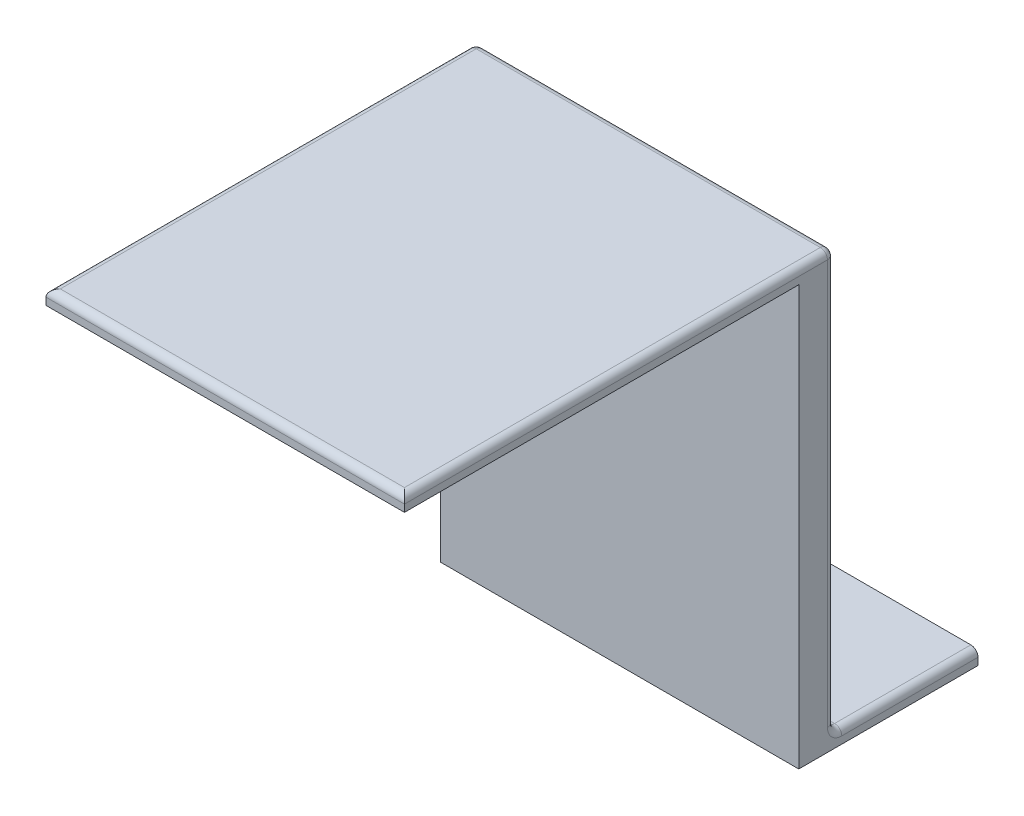
SolidWorks part; units mm, degrees
ref_plane "前视基准面" through (0, 0, 0) normal (0, 0, 1) x (1, 0, 0)
ref_plane "上视基准面" through (0, 0, 0) normal (0, 1, 0) x (1, 0, 0)
ref_plane "右视基准面" through (0, 0, 0) normal (1, 0, 0) x (0, 0, -1)
sketch "草图1" plane through (0, 0, 0) normal (0, 0, 1) x (1, 0, 0)
  line L1 (-18.1818, 18.568) -> (31.8182, 18.568)
  line L2 (-18.1818, 18.568) -> (-18.1818, -41.932)
  line L3 (-18.1818, -41.932) -> (31.8182, -41.932)
  line L4 (31.8182, 18.568) -> (31.8182, -41.932)
  dimension "D1" = 50
  dimension "D2" = 60.5
extrude "凸台-拉伸1" add sketch "草图1" along normal blind 60
sketch "草图3" plane through (0, 0, 60) normal (0, 0, 1) x (1, 0, 0)
  line L0 (-18.1818, 18.568) -> (-18.1818, -41.932) construction
  line L1 (31.8182, -41.932) -> (-18.1818, -41.932)
  line L2 (31.8182, -41.932) -> (31.8182, 16.568)
  line L3 (31.8182, 16.568) -> (-18.1818, 16.568)
  line L4 (-18.1818, -41.932) -> (-18.1818, 16.568)
extrude "切除-拉伸1" cut sketch "草图3" against normal blind 55
sketch "草图4" plane through (0, 0, 0) normal (0, 0, -1) x (-1, 0, 0)
  line L0 (-31.8182, -41.932) -> (-31.8182, 18.568) construction
  line L1 (18.1818, -41.932) -> (-31.8182, -41.932)
  line L2 (18.1818, -41.932) -> (18.1818, -39.932)
  line L3 (18.1818, -39.932) -> (-31.8182, -39.932)
  line L4 (-31.8182, -41.932) -> (-31.8182, -39.932)
extrude "凸台-拉伸2" add sketch "草图4" along normal blind 20
fillet "圆角5" radius 1 9 edges at (31.8182, -39.932, -10) (-18.1818, -39.932, -10) (31.8182, -10.682, 0) (-18.1818, -10.682, 0) (6.8182, -39.932, 0) (31.8182, 18.568, 30) (6.8182, 18.568, 60) (-18.1818, 18.568, 30) (6.8182, 18.568, 0)
scale "缩放比例1" scale about origin uniform scaling yes scale factor 1.7
